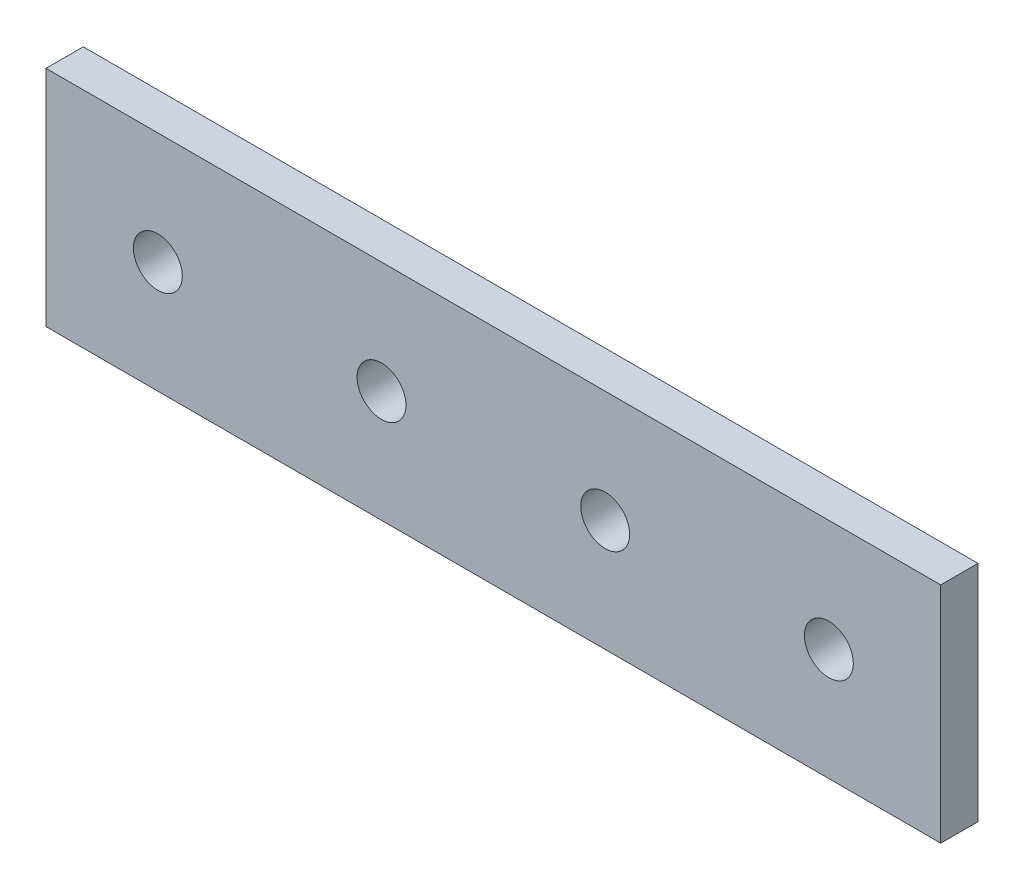
SolidWorks part; units mm, degrees
ref_plane "Front Plane" through (0, 0, 0) normal (0, 0, 1) x (1, 0, 0)
ref_plane "Top Plane" through (0, 0, 0) normal (0, 1, 0) x (1, 0, 0)
ref_plane "Right Plane" through (0, 0, 0) normal (1, 0, 0) x (0, 0, -1)
sketch "Sketch1" plane through (0, 0, 0) normal (0, 0, 1) x (1, 0, 0)
  line L0 (0, 0) -> (0, 38.1)
  line L1 (19.05, 19.05) -> (57.15, 19.05) construction
  line L2 (57.15, 19.05) -> (95.25, 19.05) construction
  line L3 (95.25, 19.05) -> (133.35, 19.05) construction
  line L4 (152.4, 38.1) -> (0, 38.1)
  line L5 (152.4, 0) -> (0, 0)
  line L7 (152.4, 38.1) -> (152.4, 0)
  circle A0 centre (19.05, 19.05) radius 4.1656
  circle A1 centre (57.15, 19.05) radius 4.1656
  circle A2 centre (95.25, 19.05) radius 4.1656
  circle A3 centre (133.35, 19.05) radius 4.1656
  dimension "D1" = 38.1
  dimension "E" = 8.3312
  dimension "D2" = 19.05
  dimension "C" = 38.1
  dimension "D3" = 19.05
  dimension "B" = 152.4
extrude "Boss-Extrude1" add sketch "Sketch1" along normal mid plane 6.35
